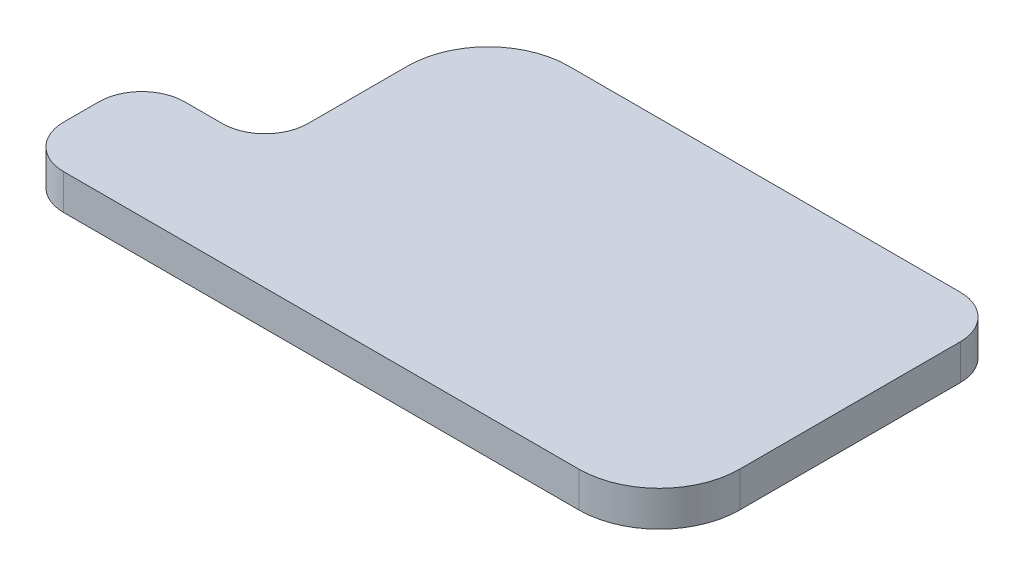
SolidWorks part; units mm, degrees
material "PE High Density"
ref_plane "Front Plane" through (0, 0, 0) normal (0, 0, 1) x (1, 0, 0)
ref_plane "Top Plane" through (0, 0, 0) normal (0, 1, 0) x (1, 0, 0)
ref_plane "Right Plane" through (0, 0, 0) normal (1, 0, 0) x (0, 0, -1)
sketch "Sketch1" plane through (0, 0, 0) normal (0, 1, 0) x (1, 0, 0)
  line L0 (0, 0) -> (23.8, 0)
  line L6 (0, 0) -> (0, 4.51)
  line L7 (0, 4.51) -> (4.6, 4.51)
  line L8 (4.6, 4.51) -> (4.6, 12.82)
  line L9 (4.6, 12.82) -> (23.8, 12.82)
  line L10 (23.8, 12.82) -> (23.8, 0)
  dimension "D1" = 12.82
  dimension "D5" = 23.8
  dimension "D6" = 4.51
  dimension "D7" = 19.2
extrude "Boss-Extrude1" add sketch "Sketch1" along normal blind 1.32 contours L0
fillet "Fillet1" radius 3 2 edges at (4.6, 0.66, -12.82) (23.8, 0.66, 0)
fillet "Fillet2" radius 1.6 4 edges at (23.8, 0.66, -12.82) (4.6, 0.66, -4.51) (0, 0.66, 0) (0, 0.66, -4.51)
